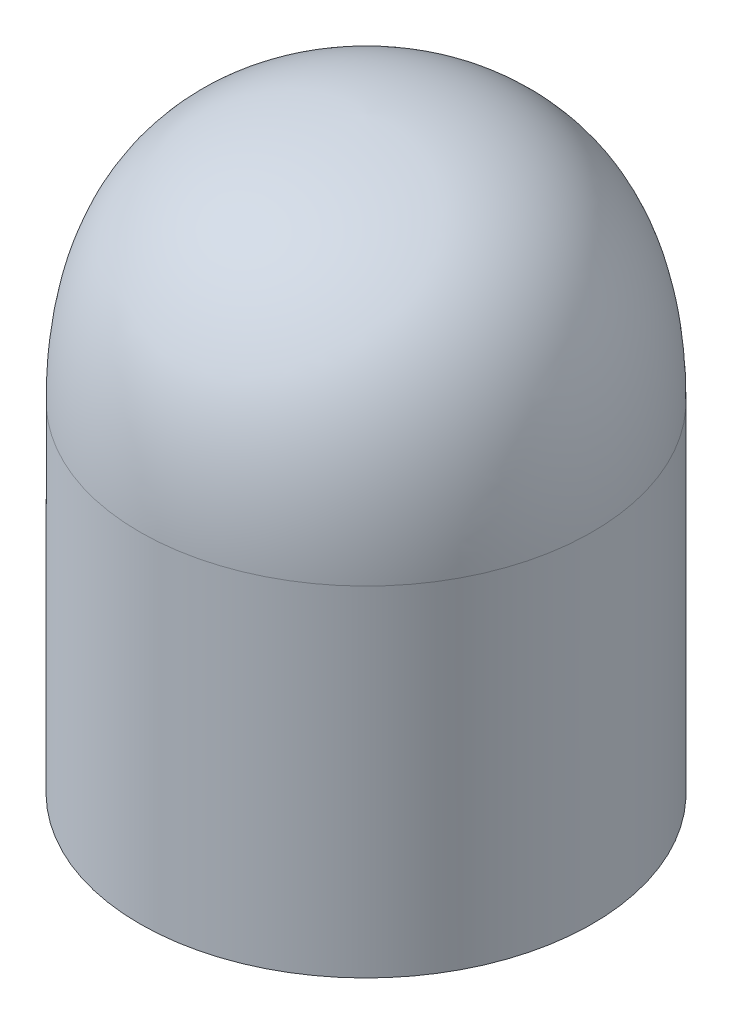
SolidWorks part; units mm, degrees
ref_plane "前视基准面" through (0, 0, 0) normal (0, 0, 1) x (1, 0, 0)
ref_plane "上视基准面" through (0, 0, 0) normal (0, 1, 0) x (1, 0, 0)
ref_plane "右视基准面" through (0, 0, 0) normal (1, 0, 0) x (0, 0, -1)
sketch "草图1" plane through (0, 0, 0) normal (0, 1, 0) x (1, 0, 0)
  circle A0 centre (0, 0) radius 48
  circle A1 centre (0, 0) radius 50
extrude "凸台-拉伸1" add sketch "草图1" along normal blind 75
sketch "草图3" plane through (0, 0, 0) normal (0, 0, 1) x (1, 0, 0)
  line L0 (0, 0) -> (0, 75) construction
  line L1 (0, 75) -> (-50, 75) construction
  line L2 (-50, 75) -> (-50, 0) construction
  line L3 (0, 75) -> (0, 130) construction
  line L4 (-50, 72.2213) -> (-50, 130) construction
  line L5 (-50, 75) -> (-50, 0) construction
  line L8 (-50, 75) -> (-48, 75)
  line L9 (0, 130) -> (0, 128)
  spline S0 degree 3 poles (-50, 75) (-49.973, 112.8703) (-30.8316, 129.1467) (0, 130) knots 0 0 0 0 1 1 1 1
  spline S1 degree 3 poles (-48, 75) (-47.112, 108.9377) (-31.0112, 127.2803) (0, 128) knots 0 0 0 0 1 1 1 1
revolve "旋转1" add sketch "草图3" angle 360 about L3
